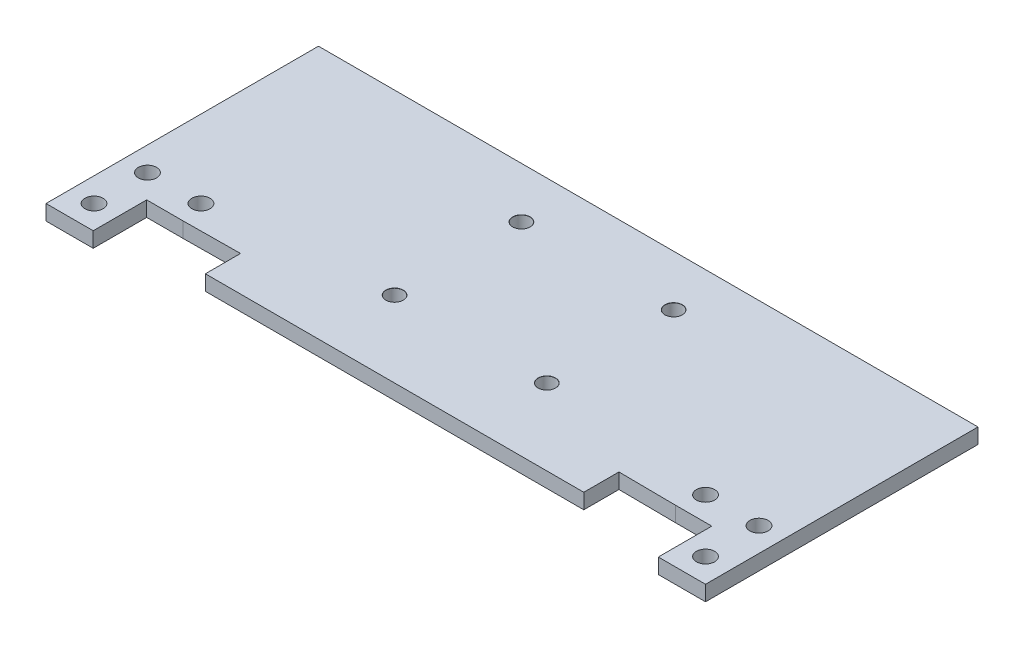
SolidWorks part; units mm, degrees
ref_plane "Front Plane" through (0, 0, 0) normal (0, 0, 1) x (1, 0, 0)
ref_plane "Top Plane" through (0, 0, 0) normal (0, 1, 0) x (1, 0, 0)
ref_plane "Right Plane" through (0, 0, 0) normal (1, 0, 0) x (0, 0, -1)
sketch "Sketch1" plane through (0, 0, 0) normal (1, 0, 0) x (0, 0, -1)
  line L2 (3.71, 3) -> (53.71, 3)
  line L6 (3.71, 0) -> (53.71, 0)
  line L7 (53.71, 0) -> (53.71, 3)
  line L8 (3.71, 3) -> (3.71, 0)
  dimension "D1" = 3.71
  dimension "D3" = 50
  dimension "D6" = 3
extrude "Boss-Extrude1" add sketch "Sketch1" along normal blind 130
hole_wizard "M3 Clearance Hole2" positions "Sketch5" profile "Sketch6" hole size "M3" standard "ANSI Metric" end condition through all
sketch "Sketch5" plane through (0, 3, 0) normal (0, 1, 0) x (1, 0, 0)
  line L0 (65, 53.71) -> (65, 43.71) construction
  line L1 (130, 53.71) -> (0, 53.71) construction
  line L3 (50, 43.71) -> (80, 43.71) construction
  line L4 (80, 43.71) -> (80, 18.71) construction
  line L5 (80, 18.71) -> (50, 18.71) construction
  line L6 (50, 18.71) -> (50, 43.71) construction
  point P9 (50, 43.71)
  point P11 (80, 43.71)
  point P13 (50, 18.71)
  point P15 (80, 18.71)
  point P25 (65, 43.71)
  dimension "D1" = 30
  dimension "D2" = 25
  dimension "D3" = 10
sketch "Sketch6" plane through (80, 3, -18.71) normal (1, 0, 0) x (0, 0, 1)
  line L0 (0, 0) -> (0, 3)
  line L1 (0, 3) -> (1.7, 3)
  line L2 (1.7, 3) -> (1.7, 0.025)
  line L3 (1.7, 0.025) -> (1.725, 0)
  line L5 (1.725, 0) -> (0, 0)
  line L6 (-1.7, 0.025) -> (-1.725, 0) construction
  line L11 (0, -6.35) -> (0, 107.95) construction
  dimension "Thru Hole Dia." = 3.4
  dimension "Thru Hole Depth" = 3
  dimension "Near C'Sink Dia." = 3.45
  dimension "Near C'Sink Angle" = 90
sketch "Sketch7" plane through (0, 0, 0) normal (0, -1, 0) x (1, 0, 0)
  line L0 (130, -3.71) -> (0, -3.71) construction
  line L1 (130, -3.71) -> (0, -3.71)
  line L2 (108.1956, -3.71) -> (108.1956, 0.0001)
  line L3 (108.1956, 0.0001) -> (130, 0.0001)
  line L4 (130, 13.0001) -> (130, -19.9999) construction
  line L5 (130, 0.0001) -> (130, -3.71)
  line L6 (125.2699, -4.73) -> (130, -4.73) construction
  line L7 (130, -3.71) -> (130, -53.71) construction
  line L8 (119.0978, 0.0001) -> (119.0978, -4.73) construction
  line L9 (120.4956, -10.3397) -> (120.4956, 4.3493) construction
  line L10 (120.4956, -10.3397) -> (120.4956, 4.3493) construction
  line L11 (65, -3.71) -> (65, -53.71) construction
  line L12 (130, -53.71) -> (0, -53.71) construction
  line L13 (0, 0.0001) -> (0, -3.71)
  line L14 (21.8044, 0.0001) -> (0, 0.0001)
  line L15 (21.8044, -3.71) -> (21.8044, 0.0001)
  circle A0 centre (125.2699, -4.73) radius 1.8 construction
  circle A1 centre (125.2699, -4.73) radius 1.8 construction
  line M17 (130, -3.71) -> (0, -3.71)
  dimension "D1" = 12.3
extrude "Boss-Extrude2" add sketch "Sketch7" against normal up to surface (3 mm away) contours L5 L3 L2 M17 | L15 L14 L13 M17 up to face at (50, 3, -41.985)
sketch "Sketch9" plane through (0, 3, 0) normal (0, 1, 0) x (1, 0, 0)
  line L0 (120.4956, 10.3397) -> (113.4956, 10.3397) construction
  line L1 (120.4956, 10.3397) -> (120.4956, -4.3493) construction
  line L2 (120.4956, 10.3397) -> (113.4956, 10.3397)
  line L3 (120.4956, 10.3397) -> (120.4956, -4.3493)
  line L4 (102.4956, 0.9897) -> (102.4956, 10.4376) construction
  line L5 (102.4956, 0.9897) -> (102.4956, 10.4376)
  line L6 (113.4956, 10.3397) -> (102.4956, 10.4376)
  line L7 (102.4956, 0.9897) -> (120.4956, -4.3493)
  line L8 (102.2956, 0.8404) -> (102.2956, 10.6394)
  line L9 (113.4965, 10.5397) -> (102.2956, 10.6394)
  line L10 (120.6956, 10.5397) -> (113.4965, 10.5397)
  line L11 (120.6956, 10.5397) -> (120.6956, -4.6173)
  line L12 (102.2956, 0.8404) -> (120.6956, -4.6173)
  line L13 (108.1956, 3.71) -> (21.8044, 3.71) construction
  line L14 (130, 53.71) -> (0, 53.71) construction
  line L15 (108.1956, 3.71) -> (21.8044, 3.71) construction
  line L16 (130, 53.71) -> (0, 53.71) construction
  line L17 (65, 53.71) -> (65, 3.71) construction
  line L18 (9.3044, 10.5397) -> (9.3044, -4.6173)
  line L19 (9.3044, 10.5397) -> (16.5035, 10.5397)
  line L20 (16.5035, 10.5397) -> (27.7044, 10.6394)
  line L21 (27.7044, 0.8404) -> (27.7044, 10.6394)
  line L22 (27.7044, 0.8404) -> (9.3044, -4.6173)
  line M8 (21.8044, -0.0001) -> (21.8044, 3.71)
  line M9 (21.8044, 3.71) -> (108.1956, 3.71)
  line M10 (108.1956, 3.71) -> (108.1956, -0.0001)
  dimension "D1" = 0.2
extrude "Cut-Extrude1" cut sketch "Sketch9" against normal through all contours L2 L6 L5 L3 M9 | L5 L7 L3 M9 | L8 L12 L11 L3 L7 L5 M10 M9 | L11 L10 L9 L8 L5 L6 L2 L3 M9 | L21 L20 L19 L18 M9 | L22 L21 L18 M9 M8
sketch "Sketch10" plane through (0, 3, 0) normal (0, 1, 0) x (1, 0, 0)
  point P0 (125.2699, 4.73)
  point P3 (125.2699, 15.2698)
  point P6 (114.7301, 15.2698)
hole_wizard "M3 Clearance Hole3" positions "Sketch10" profile "Sketch11" hole size "M3" standard "ANSI Metric" end condition through all
sketch "Sketch11" plane through (125.2699, 3, -4.73) normal (1, 0, 0) x (0, 0, 1)
  line L0 (0, 0) -> (0, 3)
  line L1 (0, 3) -> (1.8, 3)
  line L2 (1.8, 3) -> (1.8, 0)
  line L5 (1.8, 0) -> (0, 0)
  line L11 (0, -6.35) -> (0, 107.95) construction
  dimension "Thru Hole Dia." = 3.6
  dimension "Thru Hole Depth" = 3
ref_plane "Plane1" through (65, 0, 0) normal (1, 0, 0) x (0, 0, -1)
mirror "Mirror1" about plane through (65, 0, 0) normal (1, 0, 0) of "M3 Clearance Hole3"
